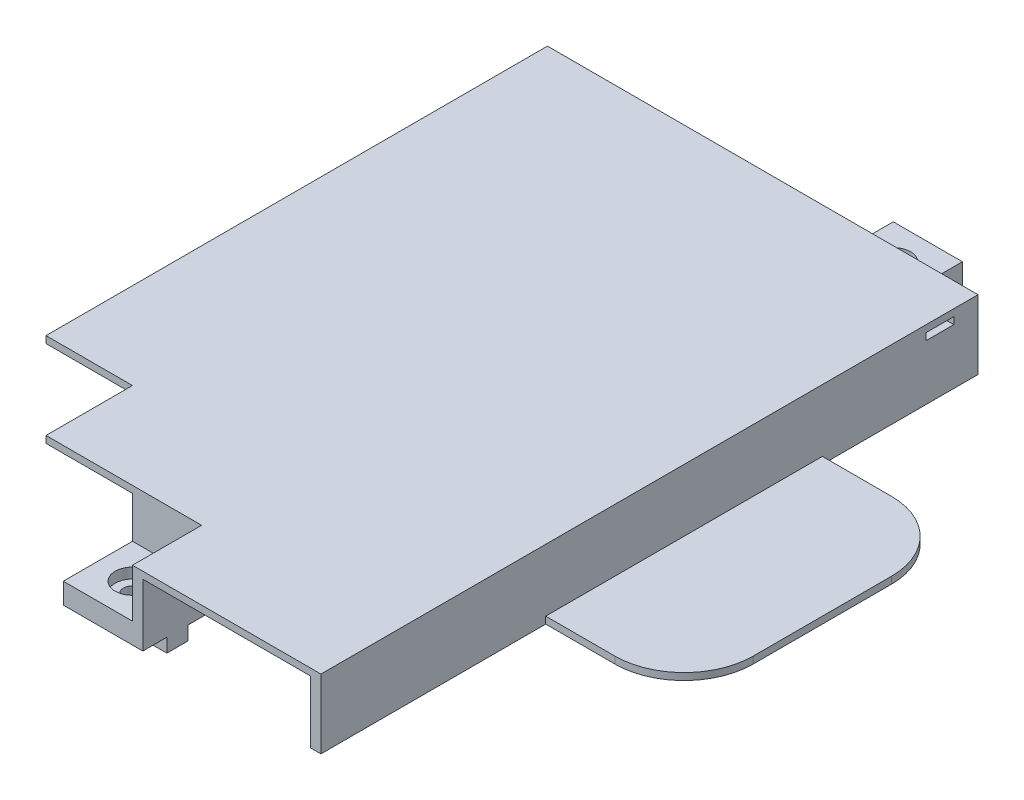
SolidWorks part; units mm, degrees
ref_plane "前视基准面" through (0, 0, 0) normal (0, 0, 1) x (1, 0, 0)
ref_plane "上视基准面" through (0, 0, 0) normal (0, 1, 0) x (1, 0, 0)
ref_plane "右视基准面" through (0, 0, 0) normal (1, 0, 0) x (0, 0, -1)
other "Configuration Table"
sketch "草图1" plane through (0, 0, 0) normal (0, 1, 0) x (1, 0, 0)
  line L5 (-90, -85) -> (90, -85)
  line L6 (-90, -85) -> (-90, 85)
  line L7 (-90, 85) -> (90, 85)
  line L8 (90, -85) -> (90, 85)
extrude "凸台-拉伸1" add sketch "草图1" along normal blind 2 contours L6 L5 L8 L7
sketch "草图2" plane through (0, 0, 0) normal (0, 1, 0) x (1, 0, 0)
  line L0 (90, -85) -> (90, 85) construction
  line L1 (-90, 85) -> (90, 85)
  line L2 (-90, 85) -> (-90, 83)
  line L3 (-90, 83) -> (90, 83)
  line L4 (90, 85) -> (90, 83)
  line L5 (88, -83) -> (-88, -83)
  line L6 (-90, -85) -> (-88, -85)
  line L7 (-90, -85) -> (-90, 83)
  line L8 (-90, 83) -> (-88, 83)
  line L9 (-88, -85) -> (-88, 83)
  line L10 (90, -85) -> (-88, -85)
  line L11 (90, -85) -> (90, -83)
  line L13 (-88, -85) -> (-88, -83)
  line L14 (90, 83) -> (88, 83)
  line L15 (90, 83) -> (90, -83)
  line L16 (90, -83) -> (88, -83)
  line L17 (88, 83) -> (88, -83)
extrude "凸台-拉伸2" add sketch "草图2" against normal blind 18 contours L4 L1 L2 L3 | L6 L9 L3 L7 | L3 L17 L16 L15 | L11 L16 L5 L9 L10
sketch "草图4" plane through (0, 2, 0) normal (0, 1, 0) x (1, 0, 0)
  line L0 (0, 0) -> (0, -85)
  line L1 (-90, -85) -> (90, -85) construction
  line L2 (0, 0) -> (-90, 0)
  line L3 (-90, -85) -> (-90, 85) construction
  line L5 (-110, 0) -> (-110, 10)
  line L6 (-90, 0) -> (-90, -10)
  line L7 (-10, -95) -> (-10, -85)
  line L8 (10, -95) -> (10, -105)
  line L9 (-10, -85) -> (10, -85)
  line L10 (-10, -85) -> (-10, -105)
  line L11 (-10, -105) -> (10, -105)
  line L12 (10, -85) -> (10, -105)
  line L14 (-110, 10) -> (-90, 10)
  line L15 (-110, 10) -> (-110, -10)
  line L16 (-110, -10) -> (-90, -10)
  line L17 (-90, 10) -> (-90, -10)
  line M17 (-90, -85) -> (90, -85)
extrude "凸台-拉伸3" add sketch "草图4" against normal blind 20 contours L12 L7 L10 L11 L8 M17 | L15 L14 L17 L16
sketch "草图5" plane through (0, 2, 0) normal (0, 1, 0) x (1, 0, 0)
  line L1 (-110, 10) -> (-90, 10)
  line L2 (-110, 10) -> (-110, -10)
  line L3 (-110, -10) -> (-90, -10)
  line L4 (-90, 10) -> (-90, -10)
  line L5 (-10, -85) -> (10, -85)
  line L6 (-10, -85) -> (-10, -105)
  line L7 (-10, -105) -> (10, -105)
  line L8 (10, -85) -> (10, -105)
extrude "切除-拉伸1" cut sketch "草图5" against normal blind 14 contours L6 L5 L8 L7 | L2 L1 L4 L3
sketch "草图6" plane through (0, 0, 0) normal (0, -1, 0) x (1, 0, 0)
  line L0 (88, 83) -> (88, 82)
  line L2 (-88, -83) -> (-88, 83)
  line L3 (-88, 83) -> (88, 83)
  line L4 (88, -83) -> (88, 83)
  line L6 (-88, -83) -> (-87, -83)
  line L8 (-88, -83) -> (88, -83)
  line L9 (-87, -82) -> (87, -82)
  line L10 (-87, -82) -> (-87, 82)
  line L11 (-87, 82) -> (87, 82)
  line L12 (87, -82) -> (87, 82)
  line M13 (-88, -83) -> (88, -83)
  line M14 (88, -83) -> (88, 83)
  line M15 (88, 83) -> (-88, 83)
  line M16 (-88, 83) -> (-88, -83)
extrude "凸台-拉伸4" add sketch "草图6" along normal blind 18 contours L12 L9 L10 L11 M16 M13 M14 M15
sketch "草图7" plane through (0, -18, 0) normal (0, -1, 0) x (-1, 0, 0)
  line L0 (0, 0) -> (0, 85)
  line L1 (90, 85) -> (-90, 85) construction
  line L3 (0, 105) -> (-10, 105)
  line L4 (0, 85) -> (10, 85)
  line L6 (10, 85) -> (-10, 85)
  line L7 (10, 85) -> (10, 105)
  line L8 (10, 105) -> (-10, 105)
  line L9 (-10, 85) -> (-10, 105)
extrude "凸台-拉伸5" add sketch "草图7" against normal blind 6 contours L7 L6 L9 L8
sketch "草图8" plane through (0, -18, 0) normal (0, -1, 0) x (-1, 0, 0)
  line L0 (-87, -82) -> (-90, -82)
  line L1 (-90, 85) -> (-90, -85) construction
  line L2 (-87, 82) -> (-90, 82)
  line L4 (-87, 82) -> (-90, 82)
  line L5 (-87, 82) -> (-87, -85)
  line L6 (-87, -85) -> (-90, -85)
  line L7 (-90, 82) -> (-90, -85)
  line M5 (-90, 85) -> (-90, -85)
  line M6 (-90, -85) -> (-10, -85)
  line M21 (-87, -82) -> (-87, 82)
extrude "切除-拉伸2" cut sketch "草图8" against normal blind 18 contours L2 L0 M21 M5 | L5 L0 M5 M6
sketch "草图9" plane through (0, -18, 0) normal (0, -1, 0) x (-1, 0, 0)
  line L0 (10, -105) -> (10, -85) construction
  line L1 (-87, -82) -> (-10, -82)
  line L2 (-87, -82) -> (-87, -85)
  line L3 (-87, -85) -> (-10, -85)
  line L4 (-10, -82) -> (-10, -85)
  line L5 (87, -82) -> (10, -82)
  line L6 (87, -82) -> (87, -85)
  line L7 (87, -85) -> (10, -85)
  line L8 (10, -82) -> (10, -85)
  line L9 (90, -85) -> (10, -85) construction
extrude "切除-拉伸3" cut sketch "草图9" against normal blind 18
sketch "草图10" plane through (0, 2, 0) normal (0, 1, 0) x (1, 0, 0)
  line L1 (90, -85) -> (65, -85)
  line L2 (90, -85) -> (90, -60)
  line L3 (90, -60) -> (65, -60)
  line L4 (65, -85) -> (65, -60)
extrude "切除-拉伸4" cut sketch "草图10" against normal blind 18
sketch "草图11" plane through (0, -18, 0) normal (0, -1, 0) x (-1, 0, 0)
  line L0 (0, 95) -> (0, 91.95)
  line L2 (-10, 85) -> (-10, 105) construction
  line L3 (-3.05, 98.05) -> (-10, 98.05)
  line L4 (10, 85) -> (10, 105) construction
  line L5 (10, 95) -> (10, 91.95)
  line L6 (-10, 95) -> (-10, 98.05)
  line L7 (0, 91.95) -> (3.05, 91.95)
  line L9 (10, 91.95) -> (10, 98.05)
  line L11 (-10, 91.95) -> (-10, 98.05)
  line L12 (0, 95) -> (0, 98.05)
  line L13 (0, 98.05) -> (-3.05, 98.05)
  line L14 (-3.05, 98.05) -> (-3.05, 91.95)
  line L15 (-3.05, 91.95) -> (-10, 91.95)
  line L16 (-10, 98.05) -> (-10, 91.95)
  line L17 (3.05, 91.95) -> (10, 91.95)
  line L18 (3.05, 91.95) -> (3.05, 98.05)
  line L19 (3.05, 98.05) -> (10, 98.05)
  line L20 (10, 91.95) -> (10, 98.05)
  line M23 (-10, 105) -> (-10, 85)
extrude "凸台-拉伸6" add sketch "草图11" along normal blind 4 contours L15 L14 L3 M23 | L18 L17 L20 L19
sketch "草图12" plane through (0, -18, 0) normal (0, -1, 0) x (-1, 0, 0)
  line L0 (3.05, 91.95) -> (-3.05, 98.05)
  circle A0 centre (0, 95) radius 2.6
extrude "切除-拉伸5" cut sketch "草图12" against normal blind 6 contours L0 A0 | L0 A0
sketch "草图13" plane through (0, -12, 0) normal (0, 1, 0) x (1, 0, 0)
  circle A0 centre (0, 95) radius 5
  circle M2 centre (0, 95) radius 2.6
extrude "切除-拉伸6" cut sketch "草图13" against normal blind 3 contours A0 M2
sketch "草图14" plane through (0, -12, 0) normal (0, 1, 0) x (1, 0, 0)
  line L0 (-110, -10) -> (-90, 10)
  circle A0 centre (-100, 0) radius 5
extrude "切除-拉伸7" cut sketch "草图14" against normal blind 3 contours L0 A0
sketch "草图15" plane through (0, -15, 0) normal (0, 1, 0) x (1, 0, 0)
  circle A0 centre (-100, 0) radius 2.6
extrude "切除-拉伸8" cut sketch "草图15" against normal blind 3 contours A0
sketch "草图16" plane through (0, -18, 0) normal (0, -1, 0) x (1, 0, 0)
  line L0 (-100, 0) -> (-100, 3.05)
  line L1 (-100, 0) -> (-100, -3.05)
  line L2 (-100, -3.05) -> (-96.95, -3.05)
  line L3 (-100, 3.05) -> (-103.05, 3.05)
  line L4 (-96.95, -3.05) -> (-96.95, 10)
  line L5 (-110, 10) -> (-90, 10) construction
  line L6 (-103.05, 3.05) -> (-103.05, -10)
  line L7 (-110, -10) -> (-90, -10) construction
  line L9 (-103.05, 3.05) -> (-96.95, 3.05)
  line L10 (-103.05, 3.05) -> (-103.05, 10)
  line L11 (-103.05, 10) -> (-96.95, 10)
  line L12 (-96.95, 3.05) -> (-96.95, 10)
  line L13 (-96.95, -3.05) -> (-103.05, -3.05)
  line L14 (-96.95, -3.05) -> (-96.95, -10)
  line L15 (-96.95, -10) -> (-103.05, -10)
  line L16 (-103.05, -3.05) -> (-103.05, -10)
  line M28 (-110, -10) -> (-90, -10)
extrude "凸台-拉伸7" add sketch "草图16" along normal blind 4 contours L14 L2 L13 L6 M28 | L10 L9 L12 L11
sketch "草图17" plane through (0, -18, 0) normal (0, -1, 0) x (-1, 0, 0)
  line L0 (-10, -85) -> (10, -105)
  circle A0 centre (0, -95) radius 2.6
extrude "切除-拉伸9" cut sketch "草图17" against normal blind 6 contours L0 A0 | L0 A0
sketch "草图18" plane through (0, -12, 0) normal (0, 1, 0) x (1, 0, 0)
  circle A0 centre (0, -95) radius 5
  circle M2 centre (0, -95) radius 2.6
extrude "切除-拉伸10" cut sketch "草图18" against normal blind 3 contours A0 M2
sketch "草图19" plane through (0, -18, 0) normal (0, -1, 0) x (-1, 0, 0)
  line L0 (0, -95) -> (-3.05, -95)
  line L1 (-3.05, -95) -> (-3.05, -98.05)
  line L2 (0, -95) -> (3.05, -95)
  line L3 (3.05, -95) -> (3.05, -91.95)
  line L4 (3.05, -91.95) -> (-10, -91.95)
  line L5 (-10, -82) -> (-10, -105) construction
  line L6 (-3.05, -98.05) -> (10, -98.05)
  line L7 (10, -105) -> (10, -82) construction
  line L9 (10, -98.05) -> (3.05, -98.05)
  line L10 (10, -98.05) -> (10, -91.95)
  line L11 (10, -91.95) -> (3.05, -91.95)
  line L12 (3.05, -98.05) -> (3.05, -91.95)
  line L13 (-3.05, -98.05) -> (-10, -98.05)
  line L14 (-3.05, -98.05) -> (-3.05, -91.95)
  line L15 (-3.05, -91.95) -> (-10, -91.95)
  line L16 (-10, -98.05) -> (-10, -91.95)
  line M7 (-10, -82) -> (-10, -105)
  line M9 (10, -105) -> (10, -82)
extrude "凸台-拉伸8" add sketch "草图19" along normal blind 4 contours L12 L6 L11 L3 M9 | L1 L14 L4 L13 M7
sketch "草图20" plane through (0, 2, 0) normal (0, 1, 0) x (1, 0, 0)
  line L0 (-90, -85) -> (-10, -85)
  line L1 (-10, -85) -> (10, -85)
  line L2 (10, -85) -> (40, -85)
  line L4 (-90, -85) -> (-10, -85)
  line L5 (-90, -85) -> (-90, -105)
  line L6 (-90, -105) -> (-10, -105)
  line L7 (-10, -85) -> (-10, -105)
  line L8 (40, -85) -> (10, -85)
  line L9 (40, -85) -> (40, -105)
  line L10 (40, -105) -> (10, -105)
  line L11 (10, -85) -> (10, -105)
  line M11 (-90, -85) -> (65, -85)
extrude "凸台-拉伸9" add sketch "草图20" against normal blind 2 contours L11 L10 L9 M11 | L5 L4 L7 L6
sketch "草图21" plane through (0, 0, 0) normal (0, -1, 0) x (-1, 0, 0)
  line L1 (87, -85) -> (90, -85)
  line L2 (87, -85) -> (87, -105)
  line L3 (87, -105) -> (90, -105)
  line L4 (90, -85) -> (90, -105)
extrude "凸台-拉伸10" add sketch "草图21" along normal blind 18
sketch "草图22" plane through (0, -12, 0) normal (0, 1, 0) x (1, 0, 0)
  line L1 (-10, -105) -> (10, -105)
  line L2 (-10, -105) -> (-10, -85)
  line L3 (-10, -85) -> (10, -85)
  line L4 (10, -105) -> (10, -85)
  circle A0 centre (0, -95) radius 5
extrude "凸台-拉伸11" add sketch "草图22" along normal blind 14 contours L2 L1 L4 L3
sketch "草图23" plane through (0, 0, 0) normal (0, -1, 0) x (-1, 0, 0)
  line L1 (-10, -105) -> (-40, -105)
  line L2 (-10, -105) -> (-10, -85)
  line L3 (-10, -85) -> (-40, -85)
  line L4 (-40, -105) -> (-40, -85)
  line M12 (-40, -85) -> (-40, -105)
  line M13 (-40, -105) -> (-10, -105)
  line M14 (-10, -105) -> (-10, -82)
extrude "切除-拉伸11" cut sketch "草图23" against normal blind 14 contours L3 M14 M12 M13
sketch "草图24" plane through (0, 2, 0) normal (0, 1, 0) x (1, 0, 0)
  line L1 (90, 85) -> (70, 85)
  line L2 (90, 85) -> (90, 105)
  line L3 (90, 105) -> (70, 105)
  line L4 (70, 85) -> (70, 105)
extrude "凸台-拉伸12" add sketch "草图24" against normal blind 2 contours L2 L1 L4 L3
sketch "草图25" plane through (0, -18, 0) normal (0, -1, 0) x (-1, 0, 0)
  line L1 (-70, 85) -> (-90, 85)
  line L2 (-70, 85) -> (-70, 82)
  line L3 (-70, 82) -> (-90, 82)
  line L4 (-90, 85) -> (-90, 82)
extrude "切除-拉伸12" cut sketch "草图25" against normal blind 18
sketch "草图26" plane through (0, 0, 0) normal (0, -1, 0) x (1, 0, 0)
  line L0 (70, -85) -> (90, -85)
  line L1 (90, -105) -> (90, 60) construction
  line L2 (90, -102) -> (90, -95)
  line L3 (90, -95) -> (90, -88)
  arc A0 (90, -88) -> (90, -102) centre (90, -95) ccw
  line M14 (90, -105) -> (90, 60)
extrude "切除-拉伸13" cut sketch "草图26" against normal blind 18 contours A0 M14
sketch "草图27" plane through (0, 2, 0) normal (0, 1, 0) x (1, 0, 0)
  line L1 (70, 85) -> (67, 85)
  line L2 (70, 85) -> (70, 105)
  line L3 (70, 105) -> (67, 105)
  line L4 (67, 85) -> (67, 105)
extrude "凸台-拉伸13" add sketch "草图27" against normal blind 20 contours L2 L1 L4 L3
sketch "草图28" plane through (0, 2, 0) normal (0, 1, 0) x (1, 0, 0)
  line L1 (90, 102) -> (67, 102)
  line L2 (90, 102) -> (90, 105)
  line L3 (90, 105) -> (67, 105)
  line L4 (67, 102) -> (67, 105)
extrude "凸台-拉伸14" add sketch "草图28" against normal blind 20 contours L2 L1 L4 L3
sketch "草图29" plane through (0, 2, 0) normal (0, 1, 0) x (1, 0, 0)
  line L1 (90, 105) -> (87, 105)
  line L2 (90, 105) -> (90, 100)
  line L3 (90, 100) -> (87, 100)
  line L4 (87, 105) -> (87, 100)
extrude "切除-拉伸14" cut sketch "草图29" against normal blind 20 contours L2 L1 L4 L3
sketch "草图30" plane through (0, 2, 0) normal (0, 1, 0) x (1, 0, 0)
  line L0 (67, 85) -> (90, 85)
  line L1 (90, -60) -> (90, 88) construction
  line L2 (90, 85) -> (-34.5, 85)
  line L3 (-90, 85) -> (67, 85) construction
  line L4 (-34.5, 85) -> (-34.5, 40)
  line L5 (-34.5, 40) -> (-54.5, 40)
  line L6 (-34.5, 85) -> (-90, 85)
  line L7 (-90, 85) -> (-90, 10)
  line L8 (-74.5, 20) -> (-74.5, -20)
  line L9 (-54.5, -40) -> (-34.5, -40)
  line L10 (-34.5, -40) -> (-34.5, -85)
  line L11 (-90, 10) -> (-110, 10)
  line L12 (-110, 10) -> (-110, -10)
  line L13 (-110, -10) -> (-90, -10)
  line L14 (-90, -105) -> (-90, 85) construction
  line L15 (-90, -10) -> (-90, -105)
  line L16 (-90, -105) -> (-34.5, -105)
  line L17 (10, -105) -> (-90, -105) construction
  line L18 (-34.5, -105) -> (-34.5, -85)
  arc A0 (-54.5, 40) -> (-74.5, 20) centre (-54.5, 20) ccw
  arc A1 (-74.5, -20) -> (-54.5, -40) centre (-54.5, -20) ccw
  line M22 (67, 85) -> (-90, 85)
  line M23 (-90, 85) -> (-90, -105)
  line M24 (-90, -105) -> (10, -105)
extrude "切除-拉伸15" cut sketch "草图30" against normal blind 30 contours A1 L8 A0 L5 L4 L18 L10 L9 M22 M23 M24 | L12 L13 L11 M23
sketch "草图31" plane through (0, 2, 0) normal (0, 1, 0) x (1, 0, 0)
  line L0 (10, -105) -> (-34.5, -105) construction
  line L1 (-34.5, 85) -> (-31.5, 85)
  line L2 (-34.5, 85) -> (-34.5, -105)
  line L3 (-34.5, -105) -> (-31.5, -105)
  line L4 (-31.5, 85) -> (-31.5, -105)
extrude "凸台-拉伸15" add sketch "草图31" against normal blind 20 contours L2 L1 L4 L3
sketch "草图32" plane through (0, -18, 0) normal (0, -1, 0) x (-1, 0, 0)
  line L0 (34.5, -40) -> (54.5, -40)
  line L3 (54.5, 40) -> (34.5, 40)
  line L4 (34.5, 40) -> (34.5, -40)
  line L5 (74.5, -20) -> (74.5, 20)
  arc A0 (54.5, -40) -> (74.5, -20) centre (54.5, -20) ccw
  arc A1 (74.5, 20) -> (54.5, 40) centre (54.5, 20) ccw
extrude "凸台-拉伸16" add sketch "草图32" against normal blind 2 contours A0 L5 A1 L3 L4 L0
sketch "草图33" plane through (0, 2, 0) normal (0, 1, 0) x (1, 0, 0)
  line L1 (-34.5, -40) -> (-74.5, -40)
  line L2 (-34.5, -40) -> (-34.5, 40)
  line L3 (-34.5, 40) -> (-74.5, 40)
  line L4 (-74.5, -40) -> (-74.5, 40)
extrude "切除-拉伸16" cut sketch "草图33" against normal blind 2 contours L2 L1 L4 L3
sketch "草图34" plane through (0, 2, 0) normal (0, 1, 0) x (1, 0, 0)
  line L1 (10, -85) -> (-34.5, -85)
  line L2 (10, -85) -> (10, -105)
  line L3 (10, -105) -> (-34.5, -105)
  line L4 (-34.5, -85) -> (-34.5, -105)
extrude "切除-拉伸17" cut sketch "草图34" against normal blind 30
sketch "草图35" plane through (0, -18, 0) normal (0, -1, 0) x (-1, 0, 0)
  line L1 (10, -82) -> (-10, -82)
  line L2 (10, -82) -> (10, -85)
  line L3 (10, -85) -> (-10, -85)
  line L4 (-10, -82) -> (-10, -85)
extrude "切除-拉伸18" cut sketch "草图35" against normal blind 18 contours L2 L1 L4 L3
sketch "草图36" plane through (0, 2, 0) normal (0, 1, 0) x (1, 0, 0)
  line L0 (90, -60) -> (90, -85)
  line L1 (65, -85) -> (90, -85)
  line L2 (90, -85) -> (90, -105)
  line L3 (90, -105) -> (40, -105)
  line L4 (40, -105) -> (40, -85)
  line L5 (-34.5, -85) -> (65, -85) construction
  line L7 (20, -85) -> (20, -105)
  line L8 (20, -105) -> (40, -105)
  line L11 (20, -85) -> (20, -82)
  line L12 (20, -82) -> (40, -82)
  line L13 (40, -85) -> (40, -82)
extrude "凸台-拉伸17" add sketch "草图36" against normal blind 20 contours L4 L13 L12 L11 L7 L8
sketch "草图37" plane through (0, 2, 0) normal (0, 1, 0) x (1, 0, 0)
  line L0 (20, -85) -> (40, -105)
  circle A0 centre (30, -95) radius 2.6
extrude "切除-拉伸19" cut sketch "草图37" against normal blind 20 contours L0 A0 | L0 A0
sketch "草图38" plane through (0, 2, 0) normal (0, 1, 0) x (1, 0, 0)
  circle A0 centre (30, -95) radius 5
extrude "切除-拉伸20" cut sketch "草图38" against normal blind 17 contours A0
sketch "草图39" plane through (0, 2, 0) normal (0, 1, 0) x (1, 0, 0)
  line L1 (20, -85) -> (40, -85)
  line L2 (20, -85) -> (20, -105)
  line L3 (20, -105) -> (40, -105)
  line L4 (40, -85) -> (40, -105)
  circle A0 centre (30, -95) radius 5
extrude "切除-拉伸21" cut sketch "草图39" against normal blind 14 contours L2 L1 L4 L3
sketch "草图40" plane through (0, 2, 0) normal (0, 1, 0) x (1, 0, 0)
  line L1 (-34.5, -85) -> (20, -85)
  line L2 (-34.5, -85) -> (-34.5, -105)
  line L3 (-34.5, -105) -> (20, -105)
  line L4 (20, -85) -> (20, -105)
extrude "凸台-拉伸18" add sketch "草图40" against normal blind 2
sketch "草图42" plane through (0, -18, 0) normal (0, -1, 0) x (-1, 0, 0)
  line L0 (34.5, -105) -> (-20, -105) construction
  line L1 (-20, -82) -> (-17, -82)
  line L2 (-20, -82) -> (-20, -105)
  line L3 (-20, -105) -> (-17, -105)
  line L4 (-17, -82) -> (-17, -105)
extrude "凸台-拉伸20" add sketch "草图42" against normal blind 18 contours L2 L1 L4 L3
sketch "草图44" plane through (0, -18, 0) normal (0, -1, 0) x (-1, 0, 0)
  line L0 (-30, -95) -> (-30, -98.05)
  line L1 (-30, -98.05) -> (-33.05, -98.05)
  line L2 (-30, -95) -> (-30, -91.95)
  line L3 (-30, -91.95) -> (-26.95, -91.95)
  line L4 (-30, -91.95) -> (-40, -91.95)
  line L5 (-40, -105) -> (-40, -82) construction
  line L6 (-30, -98.05) -> (-17, -98.05)
  line L7 (-17, -82) -> (-17, -105) construction
  line L9 (-17, -98.05) -> (-26.95, -98.05)
  line L10 (-17, -98.05) -> (-17, -91.95)
  line L11 (-17, -91.95) -> (-26.95, -91.95)
  line L12 (-26.95, -98.05) -> (-26.95, -91.95)
  line L13 (-33.05, -98.05) -> (-40, -98.05)
  line L14 (-33.05, -98.05) -> (-33.05, -91.95)
  line L15 (-33.05, -91.95) -> (-40, -91.95)
  line L16 (-40, -98.05) -> (-40, -91.95)
  line M11 (-17, -105) -> (-17, -82)
extrude "凸台-拉伸21" add sketch "草图44" along normal blind 4 contours L12 L6 L11 M11 | L14 L13 L16 L15
sketch "草图45" plane through (0, 2, 0) normal (0, 1, 0) x (1, 0, 0)
  line L1 (67, 85) -> (93.3789, 85)
  line L2 (67, 85) -> (67, 106.1494)
  line L3 (67, 106.1494) -> (93.3789, 106.1494)
  line L4 (93.3789, 85) -> (93.3789, 106.1494)
extrude "切除-拉伸22" cut sketch "草图45" against normal blind 30 contours L2 L1 L4 L3
sketch "草图46" plane through (0, 0, 0) normal (0, -1, 0) x (-1, 0, 0)
  line L1 (-70, 82) -> (-90, 82)
  line L2 (-70, 82) -> (-70, 85)
  line L3 (-70, 85) -> (-90, 85)
  line L4 (-90, 82) -> (-90, 85)
extrude "凸台-拉伸22" add sketch "草图46" along normal blind 18 contours L2 L1 L4 L3
mirror "镜向1" about plane through (90, 2, 85) normal (-1, 0, 0) of "凸台-拉伸2", "凸台-拉伸4", "切除-拉伸19", "凸台-拉伸1", "切除-拉伸5", "凸台-拉伸5", "切除-拉伸4", "凸台-拉伸6", "切除-拉伸6", "切除-拉伸15", "凸台-拉伸15", "凸台-拉伸16", "凸台-拉伸17", "切除-拉伸20", "切除-拉伸21", "凸台-拉伸18", "凸台-拉伸20", "凸台-拉伸21"
sketch "草图47" plane through (0, 2, 0) normal (0, 1, 0) x (1, 0, 0)
  line L0 (-34.5, 85) -> (90, 85)
  line L1 (-34.5, 85) -> (214.5, 85) construction
  line L3 (90, 85) -> (-85.0123, 85)
  line L4 (90, 85) -> (90, -142.4653)
  line L5 (90, -142.4653) -> (-85.0123, -142.4653)
  line L6 (-85.0123, 85) -> (-85.0123, -142.4653)
  line L7 (90, 85) -> (-85.0123, 85)
  line L8 (90, 85) -> (90, 116.2888)
  line L9 (90, 116.2888) -> (-85.0123, 116.2888)
  line L10 (-85.0123, 85) -> (-85.0123, 116.2888)
  line M11 (214.5, 85) -> (-34.5, 85)
  line M12 (-34.5, 85) -> (-34.5, -105)
  line M13 (-34.5, -105) -> (20, -105)
  line M14 (20, -105) -> (20, -85)
  line M15 (20, -85) -> (65, -85)
  line M16 (65, -85) -> (65, -60)
  line M17 (65, -60) -> (115, -60)
extrude "切除-拉伸23" cut sketch "草图47" against normal blind 30 contours L10 L3 L8 L9 M11 | L4 M11 M12 M13 M14 M15 M16 M17 | L3 L6 L5 L4 M17 M16 M15 M14 M13 M12
sketch "草图48" plane through (0, -18, 0) normal (0, -1, 0) x (1, 0, 0)
  line L1 (93, -82) -> (90, -82)
  line L2 (93, -82) -> (93, 85)
  line L3 (93, 85) -> (90, 85)
  line L4 (90, -82) -> (90, 85)
  line L5 (140, 85) -> (93, 85)
  line L6 (140, 85) -> (140, 82)
  line L7 (140, 82) -> (93, 82)
  line L8 (93, 85) -> (93, 82)
  line M2 (93, 82) -> (211.5, 82)
  line M41 (140, 85) -> (90, 85)
extrude "切除-拉伸24" cut sketch "草图48" against normal blind 18 contours L6 L2 M41 M2
sketch "草图49" plane through (0, 2, 0) normal (0, 1, 0) x (1, 0, 0)
  line L1 (214.5, -40) -> (265.0979, -40)
  line L2 (214.5, -40) -> (214.5, 44.2636)
  line L3 (214.5, 44.2636) -> (265.0979, 44.2636)
  line L4 (265.0979, -40) -> (265.0979, 44.2636)
extrude "切除-拉伸25" cut sketch "草图49" against normal blind 2 contours L2 L1 L4 L3
sketch "草图50" plane through (0, -18, 0) normal (0, -1, 0) x (-1, 0, 0)
  line L1 (-163, -85) -> (-211.5, -85)
  line L2 (-163, -85) -> (-163, -82)
  line L3 (-163, -82) -> (-211.5, -82)
  line L4 (-211.5, -85) -> (-211.5, -82)
  line M8 (-140, -82) -> (-211.5, -82)
  line M34 (-211.5, -85) -> (-163, -85)
extrude "切除-拉伸26" cut sketch "草图50" against normal blind 18 contours L4 L2 M34 M8
sketch "草图51" plane through (214.5, 0, 0) normal (1, 0, 0) x (0, 0, -1)
  line L0 (85, 2) -> (78, 2)
  line L1 (85, 2) -> (-105, 2) construction
  line L2 (78, 2) -> (78, 0)
  line L3 (78, 0) -> (70, 0)
  line L5 (70, 0) -> (78, 0)
  line L6 (70, 0) -> (70, -2)
  line L7 (70, -2) -> (78, -2)
  line L8 (78, 0) -> (78, -2)
extrude "切除-拉伸27" cut sketch "草图51" against normal blind 18 contours L8 L3 L6 L7
